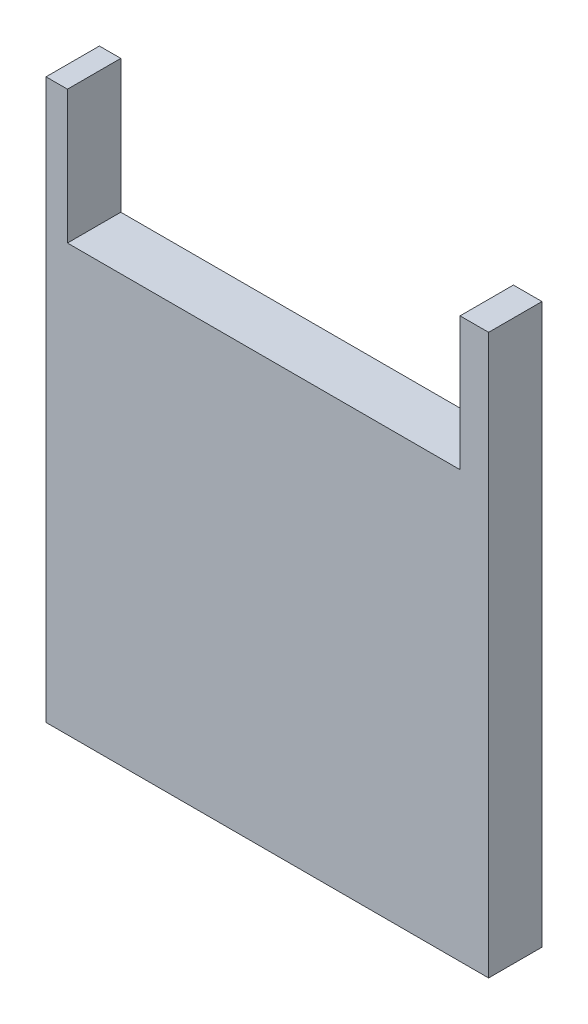
SolidWorks part; units mm, degrees
ref_plane "Front Plane" through (0, 0, 0) normal (0, 0, 1) x (1, 0, 0)
ref_plane "Top Plane" through (0, 0, 0) normal (0, 1, 0) x (1, 0, 0)
ref_plane "Right Plane" through (0, 0, 0) normal (1, 0, 0) x (0, 0, -1)
sketch "Sketch1" plane through (0, 0, 0) normal (0, 0, 1) x (1, 0, 0)
  line L0 (19.0019, -24.8898) -> (-27.5661, -24.8898)
  line L1 (-27.5661, -24.8898) -> (-27.5661, 38.0038)
  line L2 (-27.5661, 38.0038) -> (-25.1574, 38.0038)
  line L3 (-25.1574, 38.0038) -> (-25.1574, 23.0164)
  line L4 (-25.1574, 23.0164) -> (19.0019, 23.0164)
  line L5 (19.0019, 23.0164) -> (19.0019, 38.0038)
  line L6 (19.0019, 38.0038) -> (22.2135, 38.0038)
  line L7 (22.2135, 38.0038) -> (22.2135, -24.8898)
  line L8 (22.2135, -24.8898) -> (19.0019, -24.8898)
extrude "Boss-Extrude1" add sketch "Sketch1" along normal blind 6
